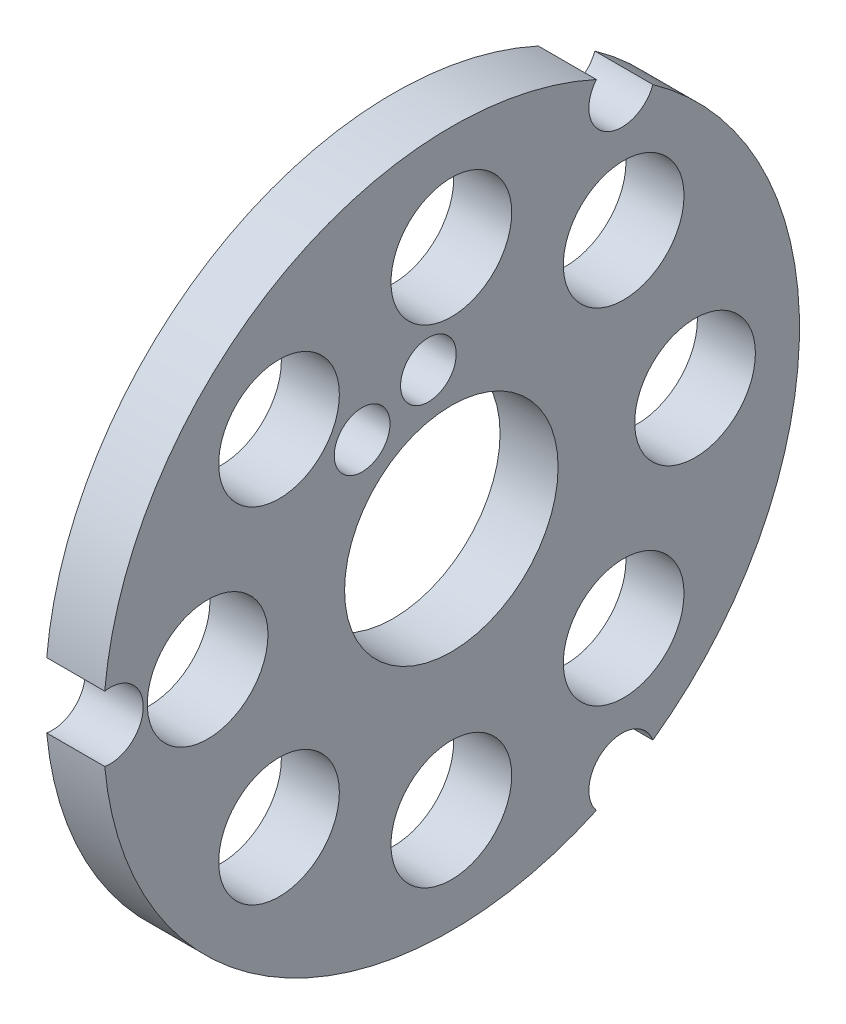
SolidWorks part; units mm, degrees
ref_plane "Front Plane" through (0, 0, 0) normal (0, 0, 1) x (1, 0, 0)
ref_plane "Top Plane" through (0, 0, 0) normal (0, 1, 0) x (1, 0, 0)
ref_plane "Right Plane" through (0, 0, 0) normal (1, 0, 0) x (0, 0, -1)
sketch "Axial profile (mm)" plane through (0, 0, 0) normal (0, 0, 1) x (1, 0, 0)
  line L0 (-110, 0) -> (75, 0) construction
  line L1 (143.7, 9.2) -> (148.7, 9.2)
  line L2 (148.7, 9.2) -> (148.7, 30)
  line L3 (148.7, 30) -> (143.7, 30)
  line L4 (143.7, 30) -> (143.7, 9.2)
revolve "Full revolution" add sketch "Axial profile (mm)" angle 360 about L0
sketch "Sketch2" plane through (0, 0, 0) normal (1, 0, 0) x (0, 0, -1)
  circle A0 centre (0, 21) radius 5.2
  circle A1 centre (-14.8492, 14.8492) radius 5.2
  circle A2 centre (-21, 0) radius 5.2
  circle A3 centre (-14.8492, -14.8492) radius 5.2
  circle A4 centre (0, -21) radius 5.2
  circle A5 centre (14.8492, -14.8492) radius 5.2
  circle A6 centre (21, 0) radius 5.2
  circle A7 centre (14.8492, 14.8492) radius 5.2
  circle A8 centre (-1.9774, 12.8487) radius 2.4
  circle A9 centre (-7.6872, 10.4836) radius 2.4
  circle A10 centre (-29.4, 0) radius 2.85
  circle A11 centre (14.7, -25.4611) radius 2.85
  circle A12 centre (14.7, 25.4611) radius 2.85
extrude "Axial holes" cut sketch "Sketch2" along normal through all and the other way through all
